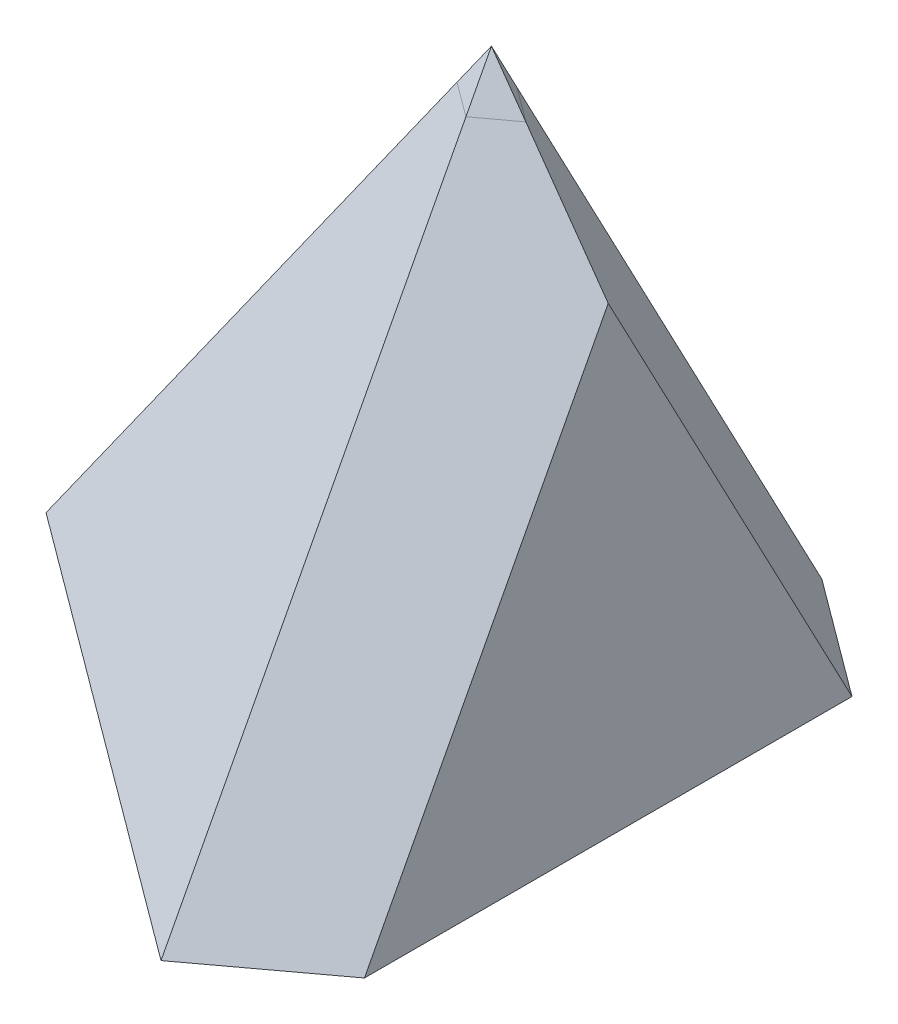
SolidWorks part; units mm, degrees
ref_plane "前视基准面" through (0, 0, 0) normal (0, 0, 1) x (1, 0, 0)
ref_plane "上视基准面" through (0, 0, 0) normal (0, 1, 0) x (1, 0, 0)
ref_plane "右视基准面" through (0, 0, 0) normal (1, 0, 0) x (0, 0, -1)
sketch "草图1" plane through (0, 0, 0) normal (0, 0, 1) x (1, 0, 0)
  line L0 (0, 48.6221) -> (0, -47.9187) construction
  line L1 (0, 48.6221) -> (59.5546, -35.1794)
  line L2 (0, 48.6221) -> (-59.5546, -35.1794)
  line L3 (-59.5546, -35.1794) -> (59.5546, -35.1794)
  line L4 (-59.5546, -35.1794) -> (-771.0694, -1036.3779)
  line L5 (-771.0694, -1036.3779) -> (771.0694, -1036.3779)
  line L6 (59.5546, -35.1794) -> (771.0694, -1036.3779)
  point P8 (0, -1036.3779)
  dimension "D1" = 35.4
  dimension "D2" = 1085
sketch "草图2" plane through (0, 0, 0) normal (1, 0, 0) x (0, 0, -1)
  line L0 (0, 48.5038) -> (-44.1211, -35.1794)
  line L1 (0, 48.6221) -> (0, -35.1794) construction
  line L2 (0, -35.1794) -> (-75.8359, -35.1794) construction
  line L3 (0, 48.6221) -> (0, -47.9187) construction
  line L4 (-44.1211, -35.1794) -> (44.1211, -35.1794)
  line L5 (0, 48.5038) -> (0, -35.1794) construction
  line L6 (0, 48.5038) -> (44.1211, -35.1794)
  line L7 (0, 48.5038) -> (0, -36.4697)
  line L8 (0, -35.1794) -> (0, -1036.3779) construction
  line L10 (-44.1211, -35.1794) -> (-571.9932, -1036.3779)
  line L11 (-571.9932, -1036.3779) -> (571.9932, -1036.3779)
  line L12 (44.1211, -35.1794) -> (571.9932, -1036.3779)
  dimension "D1" = 27.8
ref_plane "基准面4" through (0, -35.1794, 0) normal (0, -1, 0) x (-1, 0, 0)
sketch "草图4" plane through (0, -35.1794, 0) normal (0, -1, 0) x (-1, 0, 0)
  line L12 (0, 44.1211) -> (59.5546, 0)
  line L13 (-59.5546, 0) -> (0, 44.1211)
  line L14 (0, -44.1211) -> (-59.5546, 0)
  line L15 (59.5546, 0) -> (0, -44.1211)
ref_plane "基准面5" through (10.3859, 7.3809, 14.0189) normal (0.5482, 0.3896, 0.74) x (0.8363, -0.2554, -0.4851)
ref_plane "基准面6" through (0, 48.6221, 0) normal (0, -1, 0) x (-1, 0, 0)
sketch "草图6" plane through (0, 48.6221, 0) normal (0, -1, 0) x (-1, 0, 0)
  point P0 (0, 0)
loft "放样9" add profiles "草图4", "草图6"
ref_plane "基准面7" through (0, 47.6221, 0) normal (0, -1, 0) x (-1, 0, 0)
sketch "草图7" plane through (0, 47.6221, 0) normal (0, -1, 0) x (-1, 0, 0)
  line L4 (0, -44.1211) -> (59.5546, 0)
  line L5 (59.5546, 0) -> (0, 44.1211)
  line L6 (0, 44.1211) -> (-59.5546, 0)
  line L7 (-59.5546, 0) -> (0, -44.1211)
  line L8 (0, -44.1211) -> (59.5546, 0)
  line L9 (59.5546, 0) -> (0, 44.1211)
  line L10 (0, 44.1211) -> (-59.5546, 0)
  line L11 (-59.5546, 0) -> (0, -44.1211)
  dimension "D1" = 0
extrude "切除-拉伸1" cut sketch "草图7" against normal blind 10
sketch "草图8" plane through (0, 47.6221, 0) normal (0, -1, 0) x (-1, 0, 0)
  line L4 (0, -0.5265) -> (0.7107, 0)
  line L5 (-0.7107, 0) -> (0, -0.5265)
  line L6 (0, 0.5265) -> (-0.7107, 0)
  line L7 (0.7107, 0) -> (0, 0.5265)
  line L8 (0, -0.5265) -> (0.7107, 0)
  line L9 (-0.7107, 0) -> (0, -0.5265)
  line L10 (0, 0.5265) -> (-0.7107, 0)
  line L11 (0.7107, 0) -> (0, 0.5265)
  circle A0 centre (0, 0) radius 0.2681
  dimension "D1" = 0
extrude "凸台-拉伸2" add sketch "草图8" against normal blind 1 contours A0
ref_plane "基准面8" through (0, -1036.3779, 0) normal (0, -1, 0) x (-1, 0, 0)
sketch "草图9" plane through (0, -1036.3779, 0) normal (0, -1, 0) x (-1, 0, 0)
  line L0 (771.0694, 0) -> (0, -571.9932)
  line L1 (0, -571.9932) -> (-771.0694, 0)
  line L2 (771.0694, 0) -> (-771.0694, 0) construction
  line L3 (-771.0694, 0) -> (0, 571.9932)
  line L4 (0, 571.9932) -> (771.0694, 0)
loft "放样10" add profiles "草图9" section "草图9" section face at (0, -35.1794, 0)
sketch "草图10" plane through (0, -1036.3779, 0) normal (0, -1, 0) x (-1, 0, 0)
  line L8 (0, -571.9932) -> (0, 571.9932) construction
  line L9 (0, -571.9932) -> (0, 571.9932)
  line L10 (-202.2, -421.9976) -> (-202.2, 0)
  line L11 (-771.0694, 0) -> (-202.2, -421.9976)
  line L12 (-202.2, 421.9976) -> (-771.0694, 0)
  line L13 (-202.2, 0) -> (-202.2, 421.9976)
  point P19 (0, 0)
extrude "切除-拉伸2" cut sketch "草图10" against normal through all contours L13 L12 L11 L10
